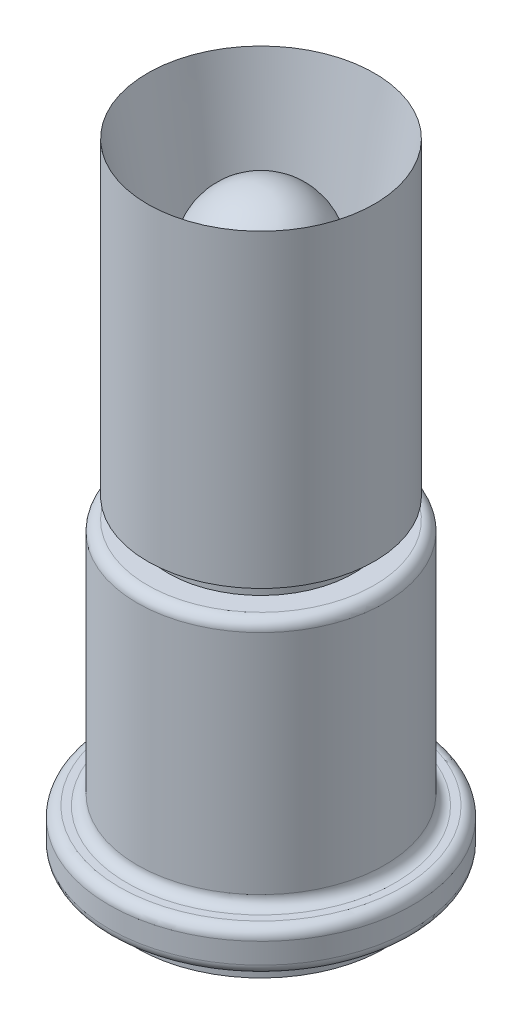
SolidWorks part; units mm, degrees
ref_plane "Front Plane" through (0, 0, 0) normal (0, 0, 1) x (1, 0, 0)
ref_plane "Top Plane" through (0, 0, 0) normal (0, 1, 0) x (1, 0, 0)
ref_plane "Right Plane" through (0, 0, 0) normal (1, 0, 0) x (0, 0, -1)
sketch "Sketch1" plane through (0, 0, 0) normal (1, 0, 0) x (0, 0, -1)
  line L0 (0, 0) -> (3.68, 0)
  line L1 (3.68, 0) -> (3.68, 1)
  line L2 (3.68, 1) -> (3, 1)
  line L3 (3, 1) -> (3, 7)
  line L4 (3, 7) -> (2.25, 7)
  line L5 (2.25, 7) -> (2.25, 7.5)
  line L6 (2.25, 7.5) -> (2.75, 7.5)
  line L7 (2.75, 7.5) -> (2.75, 15)
  line L8 (2.75, 15) -> (0, 15)
  line L9 (0, 15) -> (0, 0)
  dimension "D1" = 1
  dimension "D2" = 3
  dimension "D3" = 0.5
  dimension "D4" = 0.5
  dimension "D5" = 3.68
  dimension "D6" = 15
  dimension "D7" = 6
  dimension "D8" = 2.75
revolve "Revolve1" add sketch "Sketch1" angle 360 about L9
sketch "Sketch2" plane through (0, 0, 0) normal (1, 0, 0) x (0, 0, -1)
  line L1 (0, 0) -> (3, 0)
  line L2 (0, 0) -> (0, -0.5)
  line L3 (0, -0.5) -> (3, -0.5)
  line L4 (3, 0) -> (3, -0.5)
  line L5 (3, 1) -> (3, 7) construction
  dimension "D1" = 0.5
revolve "Revolve2" add sketch "Sketch2" angle 360 about L2
sketch "Sketch3" plane through (0, 0, 0) normal (1, 0, 0) x (0, 0, -1)
  line L1 (2.75, 15) -> (-2.75, 15) construction
  line L2 (0, -1) -> (0, 1)
  arc A0 (0, -1) -> (0, 1) centre (0, 0) ccw
  point P4 (0, -1)
  dimension "D1" = 16
revolve "Revolve3" add sketch "Sketch3" angle 360 about L2
fillet "Fillet1" radius 0.25 4 edges at (0, 0, 3.68) (0, 1, 3.68) (0, 7, 3) (0, 1, 3)
sketch "Sketch5" plane through (0, 0, 0) normal (1, 0, 0) x (0, 0, -1)
  line L0 (0, 15) -> (0, 8)
  line L1 (2.75, 15) -> (-2.75, 15) construction
  line L2 (0, 8) -> (1.5, 8)
  line L3 (1.5, 8) -> (2.75, 15)
  line L4 (2.75, 15) -> (0, 15)
  line L5 (-2.75, 7.5) -> (2.75, 7.5) construction
  dimension "D1" = 1.5
  dimension "D2" = 0.5
revolve "Cut-Revolve1" cut sketch "Sketch5" angle 360 about L0
sketch "Sketch6" plane through (0, 0, 0) normal (1, 0, 0) x (0, 0, -1)
  line L0 (1.5, 8) -> (-1.5, 8) construction
  line L1 (0, 8) -> (0, 12.5)
  line L2 (-2.75, 15) -> (2.75, 15) construction
  line L3 (1.5, 8) -> (1.5, 12.5)
  line L4 (0, 12.5) -> (0, 14)
  line L5 (0, 8) -> (1.5, 8)
  arc A0 (1.5, 12.5) -> (0, 14) centre (0, 12.5) ccw
  point P6 (0, 14)
  dimension "D1" = 3
  dimension "D2" = 1
revolve "Revolve4" add sketch "Sketch6" angle 360 about L1
